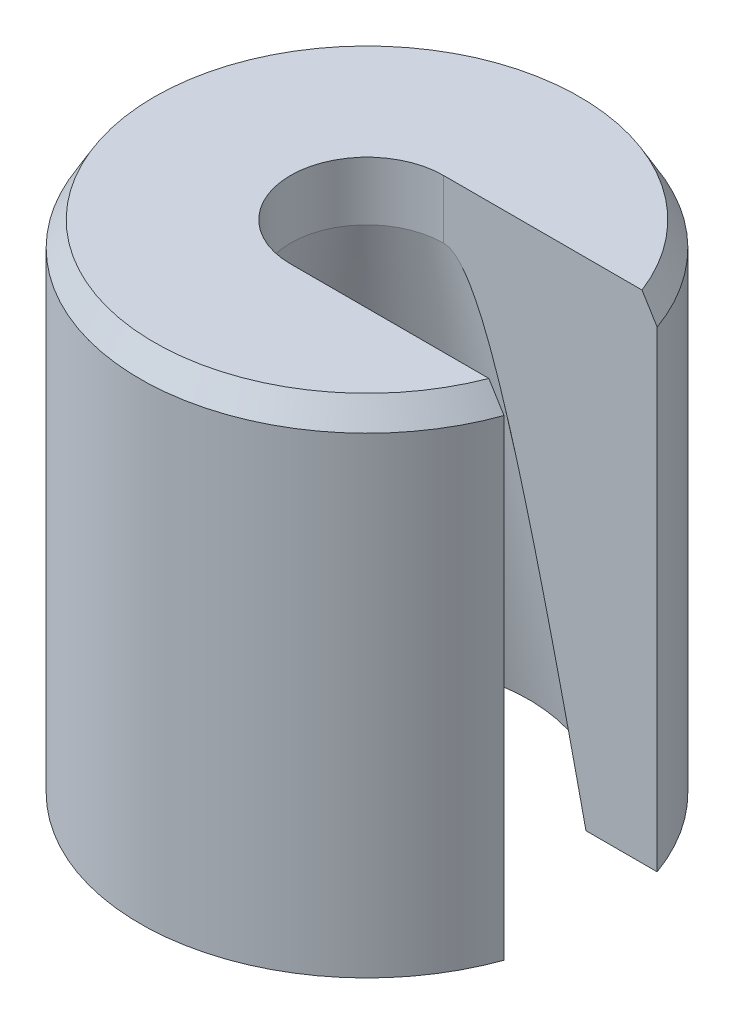
SolidWorks part; units mm, degrees
ref_plane "Front" through (0, 0, 0) normal (0, 0, 1) x (1, 0, 0)
ref_plane "Top" through (0, 0, 0) normal (0, 1, 0) x (1, 0, 0)
ref_plane "Right" through (0, 0, 0) normal (1, 0, 0) x (0, 0, -1)
sketch "Sketch1" plane through (0, 0, 0) normal (0, 1, 0) x (1, 0, 0)
  circle A0 centre (0, 0) radius 2.7
  circle A1 centre (0, 0) radius 8
  dimension "D1" = 5.4
  dimension "D2" = 16
extrude "Boss-Extrude1" add sketch "Sketch1" along normal blind 17.5
chamfer "Chamfer1" distance 3 angle 79 1 edges at (0, 0, 2.7)
chamfer "Chamfer2" distance 0.5 angle 60 1 edges at (0, 17.5, 8)
sketch "Sketch2" plane through (0, 17.5, 0) normal (0, 1, 0) x (1, 0, 0)
  line L1 (0, 2.7) -> (11.3807, 2.7)
  line L2 (0, 2.7) -> (0, -2.7)
  line L3 (0, -2.7) -> (11.3807, -2.7)
  line L4 (11.3807, 2.7) -> (11.3807, -2.7)
  circle A0 centre (0, 0) radius 2.7 construction
extrude "Cut-Extrude1" cut sketch "Sketch2" against normal blind 20
